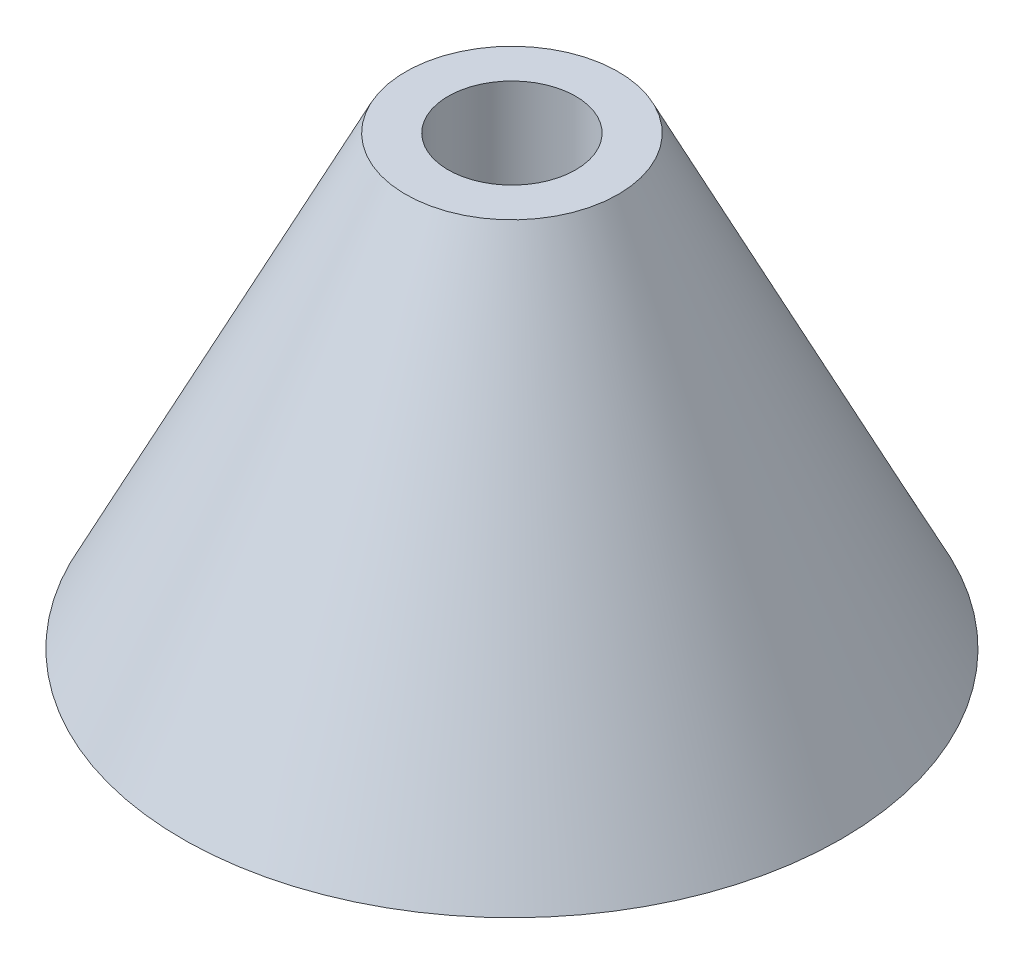
SolidWorks part; units mm, degrees
ref_plane "Front Plane" through (0, 0, 0) normal (0, 0, 1) x (1, 0, 0)
ref_plane "Top Plane" through (0, 0, 0) normal (0, 1, 0) x (1, 0, 0)
ref_plane "Right Plane" through (0, 0, 0) normal (1, 0, 0) x (0, 0, -1)
sketch "Sketch1" plane through (0, 0, 0) normal (0, 0, 1) x (1, 0, 0)
  line L0 (0, 0) -> (0, 49.1111) construction
  line L1 (6, -5.2222) -> (6, 36.7778)
  line L2 (6, 36.7778) -> (10, 36.7778)
  line L3 (10, 36.7778) -> (31, -5.2222)
  line L4 (31, -5.2222) -> (6, -5.2222)
  point P5 (0, 0)
  dimension "D1" = 6
  dimension "D2" = 10
  dimension "D3" = 42
  dimension "D4" = 25
revolve "Revolve1" add sketch "Sketch1" angle 360 about L0
